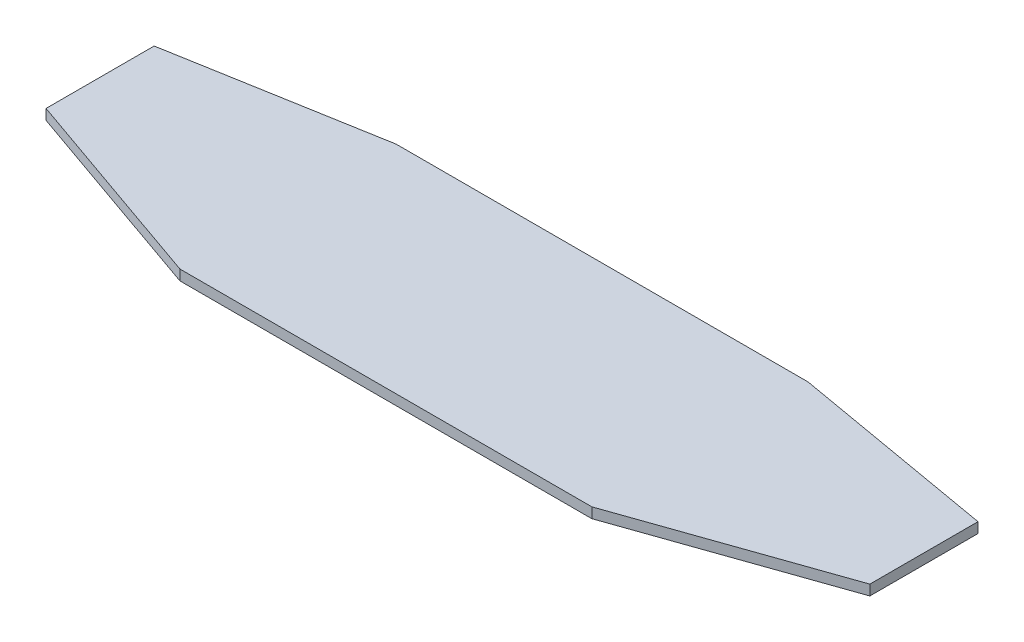
SolidWorks part; units mm, degrees
ref_plane "前视基准面" through (0, 0, 0) normal (0, 0, 1) x (1, 0, 0)
ref_plane "上视基准面" through (0, 0, 0) normal (0, 1, 0) x (1, 0, 0)
ref_plane "右视基准面" through (0, 0, 0) normal (1, 0, 0) x (0, 0, -1)
sketch "草图1" plane through (0, 0, 0) normal (0, 1, 0) x (1, 0, 0)
  line L0 (-200, 140) -> (200, 140)
  line L1 (200, 140) -> (400, 105)
  line L2 (400, 105) -> (400, 0)
  line L3 (400, 0) -> (200, -70)
  line L4 (200, -70) -> (-200, -70)
  line L5 (-200, -70) -> (-400, 0)
  line L6 (-400, 0) -> (-400, 105)
  line L7 (-400, 105) -> (-200, 140)
  dimension "D1" = 200
  dimension "D2" = 400
  dimension "D3" = 210
  dimension "D4" = 140
  dimension "D5" = 200
  dimension "D6" = 200
  dimension "D7" = 35
  dimension "D8" = 105
extrude "拉伸1" add sketch "草图1" along normal blind 10
